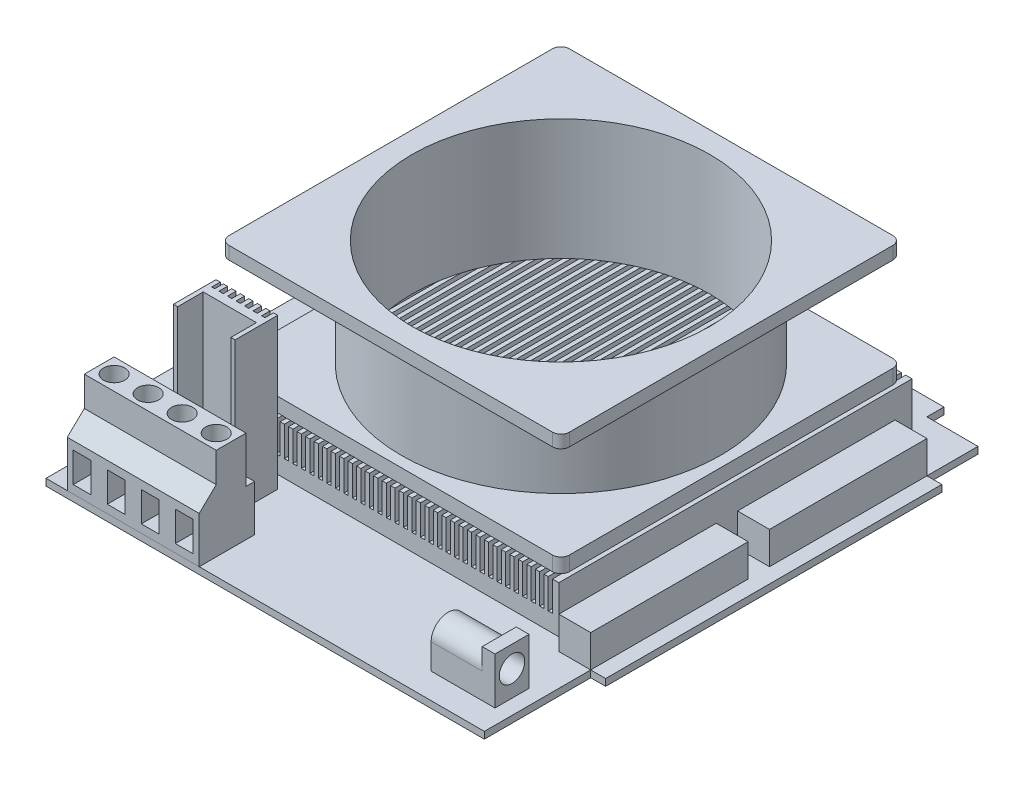
SolidWorks part; units mm, degrees
ref_plane "前视基准面" through (0, 0, 0) normal (0, 0, 1) x (1, 0, 0)
ref_plane "上视基准面" through (0, 0, 0) normal (0, 1, 0) x (1, 0, 0)
ref_plane "右视基准面" through (0, 0, 0) normal (1, 0, 0) x (0, 0, -1)
sketch "草图2" plane through (0, 0, 0) normal (0, 1, 0) x (1, 0, 0)
  line L0 (0, 84.4726) -> (0, -75.2088) construction
  line L1 (-51.5, -58) -> (51.5, -58)
  line L2 (-51.5, -58) -> (-51.5, 58)
  line L3 (-51.5, 58) -> (51.5, 58)
  line L4 (51.5, -58) -> (51.5, 58)
  line L5 (-51.5, -58) -> (51.5, 58) construction
  line L6 (-51.5, 58) -> (51.5, -58) construction
  line L7 (-39.5, 62) -> (39.5, 62)
  line L8 (-39.5, 62) -> (-39.5, -58)
  line L9 (-39.5, -58) -> (39.5, -58)
  line L10 (39.5, 62) -> (39.5, -58)
  line L11 (-55, 46) -> (55, 46)
  line L12 (-55, 46) -> (-55, -33)
  line L13 (-55, -33) -> (55, -33)
  line L14 (55, 46) -> (55, -33)
  point P0 (0, 0)
  point P10 (0, -58)
  point P11 (0, -58)
  point P18 (0, -33)
  dimension "D1" = 103
  dimension "D2" = 116
  dimension "D3" = 79
  dimension "D4" = 120
  dimension "D5" = 110
  dimension "D6" = 79
  dimension "D7" = 25
extrude "凸台-拉伸1" add sketch "草图2" along normal blind 1.6 contours L13 L2 L1 L8 | L12 L13 L2 L11 | L2 L11 L8 L3 | L10 L7 L8 L3 | L10 L11 L4 L3 | L14 L11 L4 L13 | L13 L10 L1 L4 | L13 L8 L1 L10 | L8 L13 L10 L11 | L10 L13 L4 L11 | L2 L13 L8 L11 | L8 L11 L10 L3
sketch "草图3" plane through (0, 1.6, 0) normal (0, 1, 0) x (1, 0, 0)
  line L0 (0, 64.6269) -> (0, -63.4056) construction
  line L1 (-51.5, -33) -> (-44, -33)
  line L2 (-51.5, -33) -> (-51.5, 46)
  line L3 (-51.5, 46) -> (-44, 46)
  line L4 (-44, -33) -> (-44, 46)
  line L6 (51.5, 46) -> (44, 46)
  line L7 (44, -33) -> (44, 46)
  line L8 (51.5, -33) -> (44, -33)
  line L9 (51.5, -33) -> (51.5, 46)
  dimension "D1" = 7.5
extrude "凸台-拉伸2" add sketch "草图3" along normal blind 7.6 separate body
sketch "草图4" plane through (0, 1.6, 0) normal (0, 1, 0) x (1, 0, 0)
  line L0 (-39.5, 62) -> (39.5, 62) construction
  line L1 (-41, -30) -> (41, -30)
  line L2 (-41, -30) -> (-41, 53)
  line L3 (-41, 53) -> (41, 53)
  line L4 (41, -30) -> (41, 53)
  line L5 (-41, -30) -> (41, 53) construction
  line L6 (-41, 53) -> (41, -30) construction
  line L7 (0, 70.9867) -> (0, -89.7313) construction
  point P0 (0, 11.5)
  point P5 (0, 53)
  dimension "D1" = 82
  dimension "D2" = 83
  dimension "D3" = 92
extrude "凸台-拉伸3" add sketch "草图4" along normal blind 11
sketch "草图5" plane through (0, 12.6, 0) normal (0, 1, 0) x (1, 0, 0)
  line L0 (-41, 53) -> (41, -30) construction
  line L1 (-38, -28.5) -> (38, -28.5)
  line L2 (-40, -26.5) -> (-40, 49.5)
  line L3 (-38, 51.5) -> (38, 51.5)
  line L4 (40, -26.5) -> (40, 49.5)
  line L5 (-40, -28.5) -> (40, 51.5) construction
  line L6 (-40, 51.5) -> (40, -28.5) construction
  line L7 (-41, -30) -> (41, 53) construction
  arc A0 (-40, -26.5) -> (-38, -28.5) centre (-38, -26.5) ccw
  arc A1 (38, -28.5) -> (40, -26.5) centre (38, -26.5) ccw
  arc A2 (40, 49.5) -> (38, 51.5) centre (38, 49.5) ccw
  arc A3 (-40, 49.5) -> (-38, 51.5) centre (-38, 49.5) cw
  point P0 (0, 11.5)
  point P14 (0, 11.5)
  dimension "D3" = 2
  dimension "D1" = 80
  dimension "D2" = 80
extrude "凸台-拉伸4" add sketch "草图5" along normal blind 28.4 separate body
sketch "草图8" plane through (0, 0, 30) normal (0, 0, 1) x (1, 0, 0)
  line L1 (38.5, 13.6) -> (39.5, 13.6)
  line L2 (38.5, 13.6) -> (38.5, 5.6)
  line L3 (38.5, 5.6) -> (39.5, 5.6)
  line L4 (39.5, 13.6) -> (39.5, 5.6)
  line L6 (-41, 1.6) -> (41, 1.6) construction
  line L7 (41, 12.6) -> (41, 1.6) construction
  line L8 (36.5, 13.6) -> (36.5, 5.6)
  line L9 (36.5, 13.6) -> (37.5, 13.6)
  line L10 (37.5, 13.6) -> (37.5, 5.6)
  line L11 (36.5, 5.6) -> (37.5, 5.6)
  line L12 (34.5, 13.6) -> (34.5, 5.6)
  line L13 (34.5, 13.6) -> (35.5, 13.6)
  line L14 (35.5, 13.6) -> (35.5, 5.6)
  line L15 (34.5, 5.6) -> (35.5, 5.6)
  line L16 (32.5, 13.6) -> (32.5, 5.6)
  line L17 (32.5, 13.6) -> (33.5, 13.6)
  line L18 (33.5, 13.6) -> (33.5, 5.6)
  line L19 (32.5, 5.6) -> (33.5, 5.6)
  line L20 (30.5, 13.6) -> (30.5, 5.6)
  line L21 (30.5, 13.6) -> (31.5, 13.6)
  line L22 (31.5, 13.6) -> (31.5, 5.6)
  line L23 (30.5, 5.6) -> (31.5, 5.6)
  line L24 (28.5, 13.6) -> (28.5, 5.6)
  line L25 (28.5, 13.6) -> (29.5, 13.6)
  line L26 (29.5, 13.6) -> (29.5, 5.6)
  line L27 (28.5, 5.6) -> (29.5, 5.6)
  line L28 (26.5, 13.6) -> (26.5, 5.6)
  line L29 (26.5, 13.6) -> (27.5, 13.6)
  line L30 (27.5, 13.6) -> (27.5, 5.6)
  line L31 (26.5, 5.6) -> (27.5, 5.6)
  line L32 (24.5, 13.6) -> (24.5, 5.6)
  line L33 (24.5, 13.6) -> (25.5, 13.6)
  line L34 (25.5, 13.6) -> (25.5, 5.6)
  line L35 (24.5, 5.6) -> (25.5, 5.6)
  line L36 (22.5, 13.6) -> (22.5, 5.6)
  line L37 (22.5, 13.6) -> (23.5, 13.6)
  line L38 (23.5, 13.6) -> (23.5, 5.6)
  line L39 (22.5, 5.6) -> (23.5, 5.6)
  line L40 (20.5, 13.6) -> (20.5, 5.6)
  line L41 (20.5, 13.6) -> (21.5, 13.6)
  line L42 (21.5, 13.6) -> (21.5, 5.6)
  line L43 (20.5, 5.6) -> (21.5, 5.6)
  line L44 (18.5, 13.6) -> (18.5, 5.6)
  line L45 (18.5, 13.6) -> (19.5, 13.6)
  line L46 (19.5, 13.6) -> (19.5, 5.6)
  line L47 (18.5, 5.6) -> (19.5, 5.6)
  line L48 (16.5, 13.6) -> (16.5, 5.6)
  line L49 (16.5, 13.6) -> (17.5, 13.6)
  line L50 (17.5, 13.6) -> (17.5, 5.6)
  line L51 (16.5, 5.6) -> (17.5, 5.6)
  line L52 (14.5, 13.6) -> (14.5, 5.6)
  line L53 (14.5, 13.6) -> (15.5, 13.6)
  line L54 (15.5, 13.6) -> (15.5, 5.6)
  line L55 (14.5, 5.6) -> (15.5, 5.6)
  line L56 (12.5, 13.6) -> (12.5, 5.6)
  line L57 (12.5, 13.6) -> (13.5, 13.6)
  line L58 (13.5, 13.6) -> (13.5, 5.6)
  line L59 (12.5, 5.6) -> (13.5, 5.6)
  line L60 (10.5, 13.6) -> (10.5, 5.6)
  line L61 (10.5, 13.6) -> (11.5, 13.6)
  line L62 (11.5, 13.6) -> (11.5, 5.6)
  line L63 (10.5, 5.6) -> (11.5, 5.6)
  line L64 (8.5, 13.6) -> (8.5, 5.6)
  line L65 (8.5, 13.6) -> (9.5, 13.6)
  line L66 (9.5, 13.6) -> (9.5, 5.6)
  line L67 (8.5, 5.6) -> (9.5, 5.6)
  line L68 (6.5, 13.6) -> (6.5, 5.6)
  line L69 (6.5, 13.6) -> (7.5, 13.6)
  line L70 (7.5, 13.6) -> (7.5, 5.6)
  line L71 (6.5, 5.6) -> (7.5, 5.6)
  line L72 (4.5, 13.6) -> (4.5, 5.6)
  line L73 (4.5, 13.6) -> (5.5, 13.6)
  line L74 (5.5, 13.6) -> (5.5, 5.6)
  line L75 (4.5, 5.6) -> (5.5, 5.6)
  line L76 (2.5, 13.6) -> (2.5, 5.6)
  line L77 (2.5, 13.6) -> (3.5, 13.6)
  line L78 (3.5, 13.6) -> (3.5, 5.6)
  line L79 (2.5, 5.6) -> (3.5, 5.6)
  line L80 (0.5, 13.6) -> (0.5, 5.6)
  line L81 (0.5, 13.6) -> (1.5, 13.6)
  line L82 (1.5, 13.6) -> (1.5, 5.6)
  line L83 (0.5, 5.6) -> (1.5, 5.6)
  line L84 (-1.5, 13.6) -> (-1.5, 5.6)
  line L85 (-1.5, 13.6) -> (-0.5, 13.6)
  line L86 (-0.5, 13.6) -> (-0.5, 5.6)
  line L87 (-1.5, 5.6) -> (-0.5, 5.6)
  line L88 (-3.5, 13.6) -> (-3.5, 5.6)
  line L89 (-3.5, 13.6) -> (-2.5, 13.6)
  line L90 (-2.5, 13.6) -> (-2.5, 5.6)
  line L91 (-3.5, 5.6) -> (-2.5, 5.6)
  line L92 (-5.5, 13.6) -> (-5.5, 5.6)
  line L93 (-5.5, 13.6) -> (-4.5, 13.6)
  line L94 (-4.5, 13.6) -> (-4.5, 5.6)
  line L95 (-5.5, 5.6) -> (-4.5, 5.6)
  line L96 (-7.5, 13.6) -> (-7.5, 5.6)
  line L97 (-7.5, 13.6) -> (-6.5, 13.6)
  line L98 (-6.5, 13.6) -> (-6.5, 5.6)
  line L99 (-7.5, 5.6) -> (-6.5, 5.6)
  line L100 (-9.5, 13.6) -> (-9.5, 5.6)
  line L101 (-9.5, 13.6) -> (-8.5, 13.6)
  line L102 (-8.5, 13.6) -> (-8.5, 5.6)
  line L103 (-9.5, 5.6) -> (-8.5, 5.6)
  line L104 (-11.5, 13.6) -> (-11.5, 5.6)
  line L105 (-11.5, 13.6) -> (-10.5, 13.6)
  line L106 (-10.5, 13.6) -> (-10.5, 5.6)
  line L107 (-11.5, 5.6) -> (-10.5, 5.6)
  line L108 (-13.5, 13.6) -> (-13.5, 5.6)
  line L109 (-13.5, 13.6) -> (-12.5, 13.6)
  line L110 (-12.5, 13.6) -> (-12.5, 5.6)
  line L111 (-13.5, 5.6) -> (-12.5, 5.6)
  line L112 (-15.5, 13.6) -> (-15.5, 5.6)
  line L113 (-15.5, 13.6) -> (-14.5, 13.6)
  line L114 (-14.5, 13.6) -> (-14.5, 5.6)
  line L115 (-15.5, 5.6) -> (-14.5, 5.6)
  line L116 (-17.5, 13.6) -> (-17.5, 5.6)
  line L117 (-17.5, 13.6) -> (-16.5, 13.6)
  line L118 (-16.5, 13.6) -> (-16.5, 5.6)
  line L119 (-17.5, 5.6) -> (-16.5, 5.6)
  line L120 (-19.5, 13.6) -> (-19.5, 5.6)
  line L121 (-19.5, 13.6) -> (-18.5, 13.6)
  line L122 (-18.5, 13.6) -> (-18.5, 5.6)
  line L123 (-19.5, 5.6) -> (-18.5, 5.6)
  line L124 (-21.5, 13.6) -> (-21.5, 5.6)
  line L125 (-21.5, 13.6) -> (-20.5, 13.6)
  line L126 (-20.5, 13.6) -> (-20.5, 5.6)
  line L127 (-21.5, 5.6) -> (-20.5, 5.6)
  line L128 (-23.5, 13.6) -> (-23.5, 5.6)
  line L129 (-23.5, 13.6) -> (-22.5, 13.6)
  line L130 (-22.5, 13.6) -> (-22.5, 5.6)
  line L131 (-23.5, 5.6) -> (-22.5, 5.6)
  line L132 (-25.5, 13.6) -> (-25.5, 5.6)
  line L133 (-25.5, 13.6) -> (-24.5, 13.6)
  line L134 (-24.5, 13.6) -> (-24.5, 5.6)
  line L135 (-25.5, 5.6) -> (-24.5, 5.6)
  line L136 (-27.5, 13.6) -> (-27.5, 5.6)
  line L137 (-27.5, 13.6) -> (-26.5, 13.6)
  line L138 (-26.5, 13.6) -> (-26.5, 5.6)
  line L139 (-27.5, 5.6) -> (-26.5, 5.6)
  line L140 (-29.5, 13.6) -> (-29.5, 5.6)
  line L141 (-29.5, 13.6) -> (-28.5, 13.6)
  line L142 (-28.5, 13.6) -> (-28.5, 5.6)
  line L143 (-29.5, 5.6) -> (-28.5, 5.6)
  line L144 (-31.5, 13.6) -> (-31.5, 5.6)
  line L145 (-31.5, 13.6) -> (-30.5, 13.6)
  line L146 (-30.5, 13.6) -> (-30.5, 5.6)
  line L147 (-31.5, 5.6) -> (-30.5, 5.6)
  line L148 (-33.5, 13.6) -> (-33.5, 5.6)
  line L149 (-33.5, 13.6) -> (-32.5, 13.6)
  line L150 (-32.5, 13.6) -> (-32.5, 5.6)
  line L151 (-33.5, 5.6) -> (-32.5, 5.6)
  line L152 (-35.5, 13.6) -> (-35.5, 5.6)
  line L153 (-35.5, 13.6) -> (-34.5, 13.6)
  line L154 (-34.5, 13.6) -> (-34.5, 5.6)
  line L155 (-35.5, 5.6) -> (-34.5, 5.6)
  line L156 (-37.5, 13.6) -> (-37.5, 5.6)
  line L157 (-37.5, 13.6) -> (-36.5, 13.6)
  line L158 (-36.5, 13.6) -> (-36.5, 5.6)
  line L159 (-37.5, 5.6) -> (-36.5, 5.6)
  line L160 (-39.5, 13.6) -> (-39.5, 5.6)
  line L161 (-39.5, 13.6) -> (-38.5, 13.6)
  line L162 (-38.5, 13.6) -> (-38.5, 5.6)
  line L163 (-39.5, 5.6) -> (-38.5, 5.6)
  line L164 (-41.5, 13.6) -> (-41.5, 5.6)
  line L165 (-41.5, 13.6) -> (-40.5, 13.6)
  line L166 (-40.5, 13.6) -> (-40.5, 5.6)
  line L167 (-41.5, 5.6) -> (-40.5, 5.6)
  line L168 (-43.5, 13.6) -> (-43.5, 5.6)
  line L169 (-43.5, 13.6) -> (-42.5, 13.6)
  line L170 (-42.5, 13.6) -> (-42.5, 5.6)
  line L171 (-43.5, 5.6) -> (-42.5, 5.6)
  line L172 (-45.5, 13.6) -> (-45.5, 5.6)
  line L173 (-45.5, 13.6) -> (-44.5, 13.6)
  line L174 (-44.5, 13.6) -> (-44.5, 5.6)
  line L175 (-45.5, 5.6) -> (-44.5, 5.6)
  line L176 (-47.5, 13.6) -> (-47.5, 5.6)
  line L177 (-47.5, 13.6) -> (-46.5, 13.6)
  line L178 (-46.5, 13.6) -> (-46.5, 5.6)
  line L179 (-47.5, 5.6) -> (-46.5, 5.6)
  line L180 (-49.5, 13.6) -> (-49.5, 5.6)
  line L181 (-49.5, 13.6) -> (-48.5, 13.6)
  line L182 (-48.5, 13.6) -> (-48.5, 5.6)
  line L183 (-49.5, 5.6) -> (-48.5, 5.6)
  line L184 (-51.5, 13.6) -> (-51.5, 5.6)
  line L185 (-51.5, 13.6) -> (-50.5, 13.6)
  line L186 (-50.5, 13.6) -> (-50.5, 5.6)
  line L187 (-51.5, 5.6) -> (-50.5, 5.6)
  line L188 (-53.5, 13.6) -> (-53.5, 5.6)
  line L189 (-53.5, 13.6) -> (-52.5, 13.6)
  line L190 (-52.5, 13.6) -> (-52.5, 5.6)
  line L191 (-53.5, 5.6) -> (-52.5, 5.6)
  line L192 (-55.5, 13.6) -> (-55.5, 5.6)
  line L193 (-55.5, 13.6) -> (-54.5, 13.6)
  line L194 (-54.5, 13.6) -> (-54.5, 5.6)
  line L195 (-55.5, 5.6) -> (-54.5, 5.6)
  line L196 (-57.5, 13.6) -> (-57.5, 5.6)
  line L197 (-57.5, 13.6) -> (-56.5, 13.6)
  line L198 (-56.5, 13.6) -> (-56.5, 5.6)
  line L199 (-57.5, 5.6) -> (-56.5, 5.6)
  line L200 (-59.5, 13.6) -> (-59.5, 5.6)
  line L201 (-59.5, 13.6) -> (-58.5, 13.6)
  line L202 (-58.5, 13.6) -> (-58.5, 5.6)
  line L203 (-59.5, 5.6) -> (-58.5, 5.6)
  dimension "D1" = 1
  dimension "D2" = 8
  dimension "D3" = 4
  dimension "D4" = 1.5
  dimension "D5" = 50
extrude "切除-拉伸2" cut sketch "草图8" against normal blind 115.4
sketch "草图6" plane through (0, 1.6, 0) normal (0, 1, 0) x (1, 0, 0)
  line L0 (-51.5, -58) -> (-51.5, -33) construction
  line L1 (-46.5, -45) -> (-15.5, -45)
  line L2 (-46.5, -45) -> (-46.5, -58)
  line L3 (-46.5, -58) -> (-15.5, -58)
  line L4 (-15.5, -45) -> (-15.5, -58)
  line L5 (-46.5, -45) -> (-15.5, -58) construction
  line L6 (-46.5, -58) -> (-15.5, -45) construction
  line L7 (-51.5, -58) -> (51.5, -58) construction
  point P0 (-31, -51.5)
  dimension "D1" = 31
  dimension "D2" = 13
  dimension "D3" = 5
extrude "凸台-拉伸5" add sketch "草图6" along normal blind 21.7 separate body
sketch "草图7" plane through (0, 1.6, 0) normal (0, 1, 0) x (1, 0, 0)
  line L1 (-36.5502, -43) -> (-22.0502, -43)
  line L2 (-36.5502, -43) -> (-36.5502, -33)
  line L3 (-36.5502, -33) -> (-22.0502, -33)
  line L4 (-22.0502, -43) -> (-22.0502, -33)
  line L5 (-36.5502, -43) -> (-22.0502, -33) construction
  line L6 (-36.5502, -33) -> (-22.0502, -43) construction
  line L8 (-51.5, -58) -> (51.5, -58) construction
  line L9 (-35.5502, -43) -> (-35.5502, -37)
  line L10 (-35.5502, -37) -> (-23.0502, -37)
  line L11 (-23.0502, -37) -> (-23.0502, -43)
  line L12 (-32.8502, -35) -> (-32.8502, -33)
  line L13 (-35.5502, -33) -> (-23.0502, -33)
  line L14 (-35.5502, -33) -> (-35.5502, -35)
  line L15 (-35.5502, -35) -> (-23.0502, -35)
  line L16 (-23.0502, -33) -> (-23.0502, -35)
  line L17 (-34.8502, -35) -> (-33.8502, -35)
  line L18 (-34.8502, -35) -> (-34.8502, -33)
  line L19 (-34.8502, -33) -> (-33.8502, -33)
  line L20 (-33.8502, -35) -> (-33.8502, -33)
  line L21 (-32.8502, -35) -> (-31.8502, -35)
  line L22 (-31.8502, -35) -> (-31.8502, -33)
  line L23 (-32.8502, -33) -> (-31.8502, -33)
  line L24 (-30.8502, -35) -> (-30.8502, -33)
  line L25 (-30.8502, -35) -> (-29.8502, -35)
  line L26 (-29.8502, -35) -> (-29.8502, -33)
  line L27 (-30.8502, -33) -> (-29.8502, -33)
  line L28 (-28.8502, -35) -> (-28.8502, -33)
  line L29 (-28.8502, -35) -> (-27.8502, -35)
  line L30 (-27.8502, -35) -> (-27.8502, -33)
  line L31 (-28.8502, -33) -> (-27.8502, -33)
  line L32 (-26.8502, -35) -> (-26.8502, -33)
  line L33 (-26.8502, -35) -> (-25.8502, -35)
  line L34 (-25.8502, -35) -> (-25.8502, -33)
  line L35 (-26.8502, -33) -> (-25.8502, -33)
  line L36 (-24.8502, -35) -> (-24.8502, -33)
  line L37 (-24.8502, -35) -> (-23.8502, -35)
  line L38 (-23.8502, -35) -> (-23.8502, -33)
  line L39 (-24.8502, -33) -> (-23.8502, -33)
  point P0 (-29.3002, -38)
  dimension "D1" = 14.5
  dimension "D2" = 10
  dimension "D3" = 25
  dimension "D4" = 6
  dimension "D5" = 1
  dimension "D6" = 1
  dimension "D7" = 2
  dimension "D8" = 1
  dimension "D9" = 0.7
  dimension "D10" = 6
extrude "凸台-拉伸6" add sketch "草图7" along normal blind 35.4 separate body contours L10 L11 L1 L4 L3 L2 L9 | L18 L17 L20 L19 | L12 L23 L22 L21 | L24 L27 L26 L25 | L28 L31 L30 L29 | L32 L35 L34 L33 | L36 L39 L38 L37
ref_plane "基准面1" through (0, 38, 0) normal (0, 1, 0) x (1, 0, 0)
sketch "草图9" plane through (0, 38, 0) normal (0, 1, 0) x (1, 0, 0)
  line L0 (-40, 11.5) -> (40, 11.5) construction
  line L1 (-55.6802, 63.1307) -> (75.1309, 63.1307)
  line L2 (-55.6802, 63.1307) -> (-55.6802, -42.1381)
  line L3 (-55.6802, -42.1381) -> (75.1309, -42.1381)
  line L4 (75.1309, 63.1307) -> (75.1309, -42.1381)
  line L5 (-40, 49.5) -> (-40, -26.5) construction
  line L6 (40, -26.5) -> (40, 49.5) construction
  circle A0 centre (0, 11.5) radius 37.5
  dimension "D1" = 75
extrude "切除-拉伸3" cut sketch "草图9" against normal blind 22
sketch "草图10" plane through (0, 41, 0) normal (0, 1, 0) x (1, 0, 0)
  line L0 (-40, 11.5) -> (40, 11.5) construction
  line L1 (-40, 49.5) -> (-40, -26.5) construction
  line L2 (40, -26.5) -> (40, 49.5) construction
  circle A0 centre (0, 11.5) radius 35
  dimension "D1" = 70
extrude "切除-拉伸4" cut sketch "草图10" against normal blind 45
sketch "草图11" plane through (0, 9.2, 0) normal (0, 1, 0) x (1, 0, 0)
  line L0 (-51.5, 6.5) -> (51.5, 6.5) construction
  line L1 (-51.5, 46) -> (-51.5, -33) construction
  line L2 (51.5, -33) -> (51.5, 46) construction
  line L4 (-51.5, 4) -> (51.5, 4)
  line L5 (-51.5, 4) -> (-51.5, 9)
  line L6 (-51.5, 9) -> (51.5, 9)
  line L7 (51.5, 4) -> (51.5, 9)
  point P11 (51.5, 6.5)
  dimension "D1" = 5
extrude "切除-拉伸5" cut sketch "草图11" against normal blind 25
sketch "草图13" plane through (-46.5, 0, 0) normal (-1, 0, 0) x (0, 0, 1)
  line L0 (45, 23.3) -> (45, 1.6) construction
  line L1 (45, 12.45) -> (47, 12.45)
  line L2 (45, 12.45) -> (45, 23.3)
  line L3 (45, 23.3) -> (47, 23.3)
  line L4 (47, 12.45) -> (47, 23.3)
  line L5 (45, 23.3) -> (58, 23.3) construction
  line L6 (58, 23.3) -> (54, 23.3)
  line L7 (54, 23.3) -> (54, 16.3)
  line L8 (54, 16.3) -> (58, 12.45)
  line L9 (58, 23.3) -> (58, 1.6) construction
  line L10 (58, 12.45) -> (58, 23.3)
  dimension "D1" = 2
  dimension "D2" = 7
  dimension "D3" = 4
extrude "切除-拉伸8" cut sketch "草图13" against normal blind 45
sketch "草图14" plane through (0, 23.3, 0) normal (0, 1, 0) x (1, 0, 0)
  line L0 (-46.5, -47) -> (-46.5, -54) construction
  circle A0 centre (-43, -50.5) radius 2.5
  circle A1 centre (-35, -50.5) radius 2.5
  circle A2 centre (-27, -50.5) radius 2.5
  circle A3 centre (-19, -50.5) radius 2.5
  dimension "D1" = 5
  dimension "D3" = 3.5
  dimension "D2" = 4
extrude "切除-拉伸9" cut sketch "草图14" against normal blind 15
sketch "草图15" plane through (0, 0, 58) normal (0, 0, 1) x (1, 0, 0)
  line L0 (-46.5, 12.45) -> (-46.5, 1.6) construction
  line L1 (-45.1, 3.525) -> (-40.9, 3.525)
  line L2 (-45.1, 3.525) -> (-45.1, 10.525)
  line L3 (-45.1, 10.525) -> (-40.9, 10.525)
  line L4 (-40.9, 3.525) -> (-40.9, 10.525)
  line L5 (-45.1, 3.525) -> (-40.9, 10.525) construction
  line L6 (-45.1, 10.525) -> (-40.9, 3.525) construction
  line L7 (-37.1, 3.525) -> (-37.1, 10.525)
  line L8 (-37.1, 3.525) -> (-32.9, 3.525)
  line L9 (-32.9, 3.525) -> (-32.9, 10.525)
  line L10 (-37.1, 10.525) -> (-32.9, 10.525)
  line L11 (-29.1, 3.525) -> (-29.1, 10.525)
  line L12 (-29.1, 3.525) -> (-24.9, 3.525)
  line L13 (-24.9, 3.525) -> (-24.9, 10.525)
  line L14 (-29.1, 10.525) -> (-24.9, 10.525)
  line L15 (-21.1, 3.525) -> (-21.1, 10.525)
  line L16 (-21.1, 3.525) -> (-16.9, 3.525)
  line L17 (-16.9, 3.525) -> (-16.9, 10.525)
  line L18 (-21.1, 10.525) -> (-16.9, 10.525)
  point P0 (-43, 7.025)
  dimension "D1" = 3.5
  dimension "D2" = 4.2
  dimension "D3" = 7
  dimension "D4" = 4
extrude "切除-拉伸10" cut sketch "草图15" against normal blind 12
ref_plane "基准面2" through (48, 0, 0) normal (1, 0, 0) x (0, 0, -1)
sketch "草图16" plane through (48, 0, 0) normal (1, 0, 0) x (0, 0, -1)
  line L0 (-33, 1.6) -> (4, 1.6) construction
  line L1 (-52, 12.6) -> (-44, 12.6)
  line L2 (-52, 12.6) -> (-52, 1.6)
  line L3 (-52, 1.6) -> (-44, 1.6)
  line L4 (-44, 12.6) -> (-44, 1.6)
  line L5 (-52, 12.6) -> (-44, 1.6) construction
  line L6 (-52, 1.6) -> (-44, 12.6) construction
  line L7 (-58, 12.45) -> (-58, 1.6) construction
  point P0 (-48, 7.1)
  dimension "D1" = 11
  dimension "D2" = 8
  dimension "D3" = 6
extrude "凸台-拉伸7" add sketch "草图16" against normal blind 15 separate body
sketch "草图17" plane through (33, 0, 0) normal (-1, 0, 0) x (0, 0, 1)
  line L0 (58, 1.6) -> (33, 1.6) construction
  line L1 (44, 12.6) -> (52, 12.6)
  line L2 (44, 12.6) -> (44, 1.6)
  line L3 (44, 1.6) -> (52, 1.6)
  line L4 (52, 12.6) -> (52, 1.6)
  circle A0 centre (48, 7.6) radius 4
  line M5 (44, 12.6) -> (44, 1.6)
  line M8 (52, 12.6) -> (44, 12.6)
  dimension "D2" = 8
  dimension "D1" = 8
  dimension "D3" = 5
extrude "切除-拉伸11" cut sketch "草图17" against normal blind 12 contours A0 L4 M8 M5
sketch "草图18" plane through (48, 0, 0) normal (1, 0, 0) x (0, 0, -1)
  line L0 (-44, 12.6) -> (-52, 12.6) construction
  circle A0 centre (-48, 7.6) radius 3
  dimension "D1" = 6
  dimension "D2" = 5
extrude "切除-拉伸12" cut sketch "草图18" against normal blind 12
